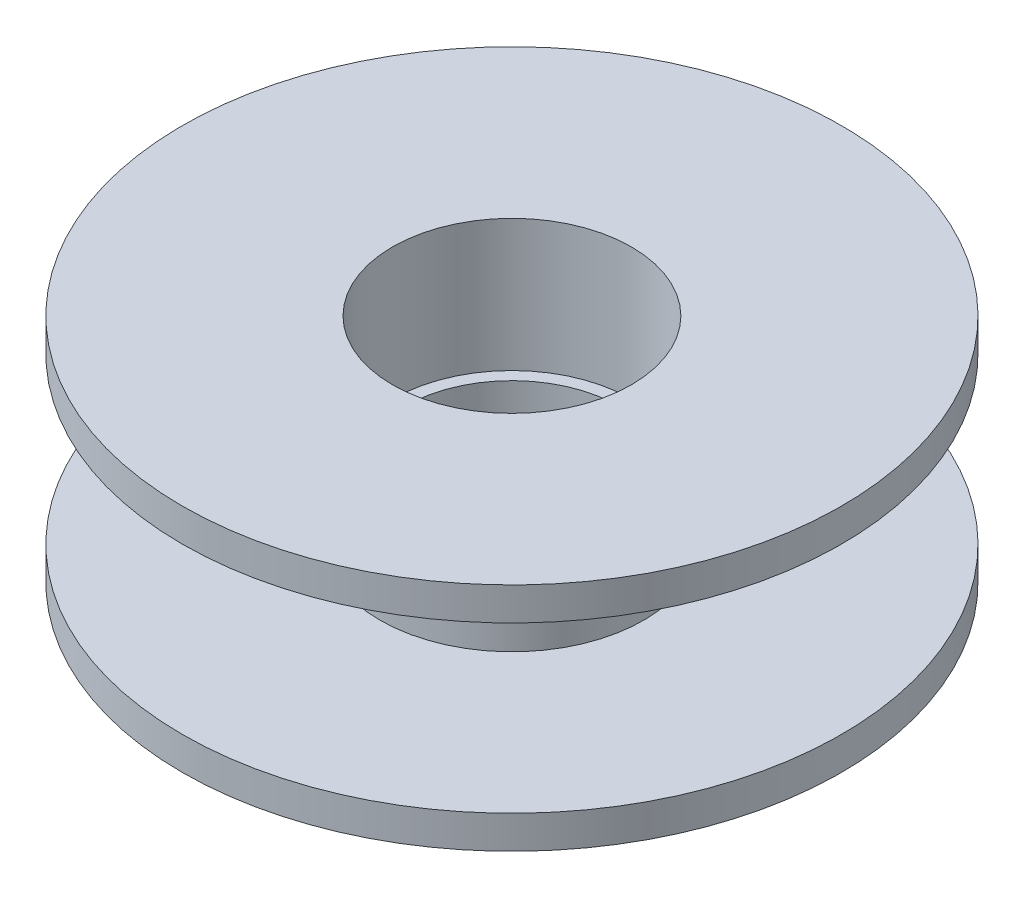
SolidWorks part; units mm, degrees
ref_plane "Front Plane" through (0, 0, 0) normal (0, 0, 1) x (1, 0, 0)
ref_plane "Top Plane" through (0, 0, 0) normal (0, 1, 0) x (1, 0, 0)
ref_plane "Right Plane" through (0, 0, 0) normal (1, 0, 0) x (0, 0, -1)
sketch "Sketch1" plane through (0, 0, 0) normal (1, 0, 0) x (0, 0, -1)
  line L0 (0, 28.0586) -> (0, -24.3494) construction
  line L5 (-16, 9.8387) -> (-40, 9.8387)
  line L6 (-40, 9.8387) -> (-40, 5.8387)
  line L7 (-40, 5.8387) -> (-13, 5.8387)
  line L8 (-13, 5.8387) -> (-13, 17.8387)
  line L14 (-16, 9.8387) -> (-16, 29.8387)
  line L15 (-16, 29.8387) -> (-14.5, 29.8387)
  line L16 (-14.5, 29.8387) -> (-14.5, 17.8387)
  line L17 (-13, 17.8387) -> (-14.5, 17.8387)
  dimension "D2" = 26
  dimension "D5" = 4
  dimension "D7" = 80
revolve "Revolve1" add sketch "Sketch1" angle 360 about L0
ref_plane "Plane1" through (0, 19.8387, 0) normal (0, 1, 0) x (1, 0, 0)
mirror "Mirror3" about plane through (0, 19.8387, 0) normal (0, 1, 0) of "Revolve1"
sketch "Sketch2" plane through (0, 17.8387, 0) normal (0, 1, 0) x (1, 0, 0)
  circle A0 centre (0, 0) radius 14.5
extrude "Cut-Extrude1" cut sketch "Sketch2" along normal blind 48
